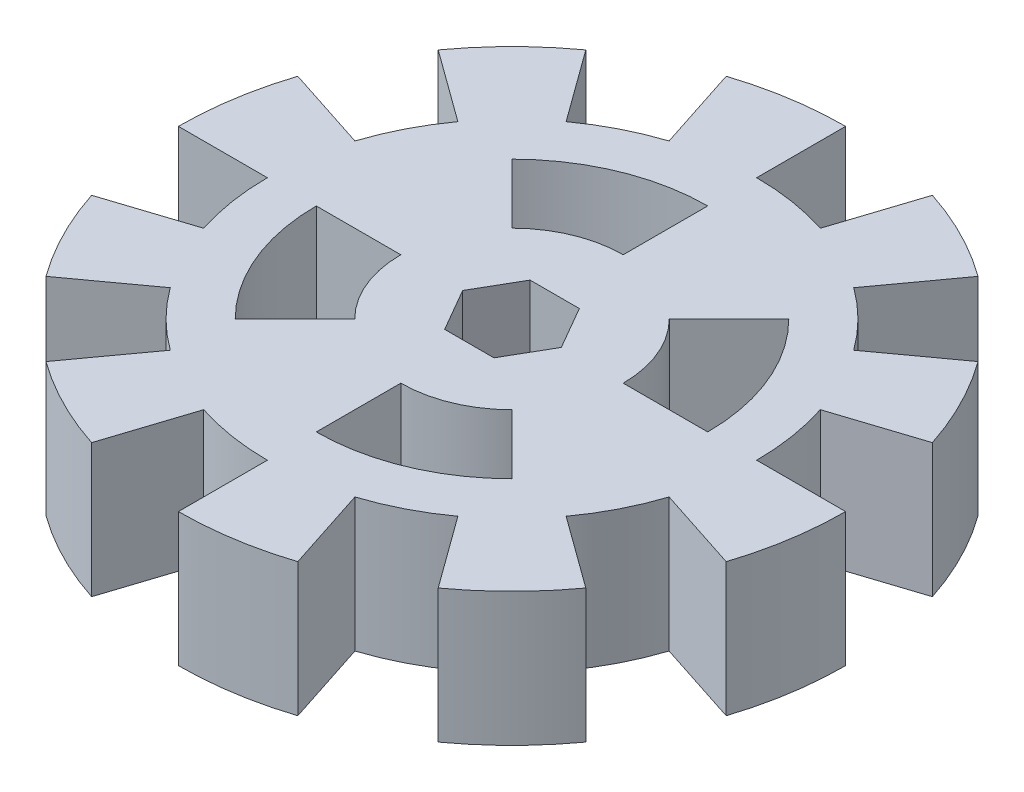
SolidWorks part; units mm, degrees
ref_plane "Front Plane" through (0, 0, 0) normal (0, 0, 1) x (1, 0, 0)
ref_plane "Top Plane" through (0, 0, 0) normal (0, 1, 0) x (1, 0, 0)
ref_plane "Right Plane" through (0, 0, 0) normal (1, 0, 0) x (0, 0, -1)
sketch "Sketch1" plane through (0, 0, 0) normal (0, 1, 0) x (1, 0, 0)
  circle A0 centre (0, 0) radius 47.625
  dimension "D1" = 95.25
extrude "Boss-Extrude1" add sketch "Sketch1" along normal blind 19.05
sketch "Sketch3" plane through (0, 19.05, 0) normal (0, 1, 0) x (1, 0, 0)
  line L0 (0, 0) -> (0, 47.625)
  line L1 (0, 0) -> (14.7169, 45.2941)
  circle A0 centre (0, 0) radius 47.625
  circle A1 centre (0, 0) radius 34.925
  circle A2 centre (0, 0) radius 47.625 construction
  circle M5 centre (0, 0) radius 47.625
  dimension "D1" = 69.85
  dimension "D2" = 18
extrude "Cut-Extrude1" cut sketch "Sketch3" against normal through all and the other way through all contours A1 L1 L0 M5
pattern_circular "CirPattern1" count 10 over 360 about axis through (0, 0, 0) along (0, 1, 0) of "Cut-Extrude1"
sketch "Sketch4" plane through (0, 19.05, 0) normal (0, 1, 0) x (1, 0, 0)
  line L0 (-3.5195, 6.096) -> (3.5195, 6.096)
  line L1 (3.5195, 6.096) -> (7.0391, 0)
  line L2 (7.0391, 0) -> (3.5195, -6.096)
  line L3 (3.5195, -6.096) -> (-3.5195, -6.096)
  line L4 (-3.5195, -6.096) -> (-7.0391, 0)
  line L5 (-7.0391, 0) -> (-3.5195, 6.096)
  point P7 (0, 6.096)
  dimension "D1" = 120
  dimension "D2" = 12.192
extrude "Cut-Extrude2" cut sketch "Sketch4" against normal blind 15.24 contours L5 L0 L1 L2 L3 L4
sketch "Sketch5" plane through (0, 3.81, 0) normal (0, 1, 0) x (1, 0, 0)
  circle A0 centre (0, 0) radius 4.064
  dimension "D1" = 8.128
extrude "Cut-Extrude3" cut sketch "Sketch5" against normal through all
sketch "Sketch6" plane through (0, 19.05, 0) normal (0, 1, 0) x (1, 0, 0)
  line L0 (0, 0) -> (0, 27.94)
  line L1 (0, 0) -> (19.7566, 19.7566)
  line L2 (0, 0) -> (27.94, 0)
  line L3 (0, 0) -> (19.7566, -19.7566)
  line L4 (0, 0) -> (0, -27.94)
  line L5 (0, 0) -> (-19.7566, -19.7566)
  line L6 (0, 0) -> (-27.94, 0)
  line L7 (0, 0) -> (-19.7566, 19.7566)
  circle A0 centre (0, 0) radius 27.94
  circle A1 centre (0, 0) radius 15.875
  point P15 (0, 0)
  dimension "D1" = 55.88
  dimension "D2" = 31.75
  dimension "D3" = 45
  dimension "D4" = 4
extrude "Cut-Extrude4" cut sketch "Sketch6" against normal through all contours A1 L0 A0 L7 | A1 L2 A0 L1 | A1 L4 A0 L3 | A1 L6 A0 L5
